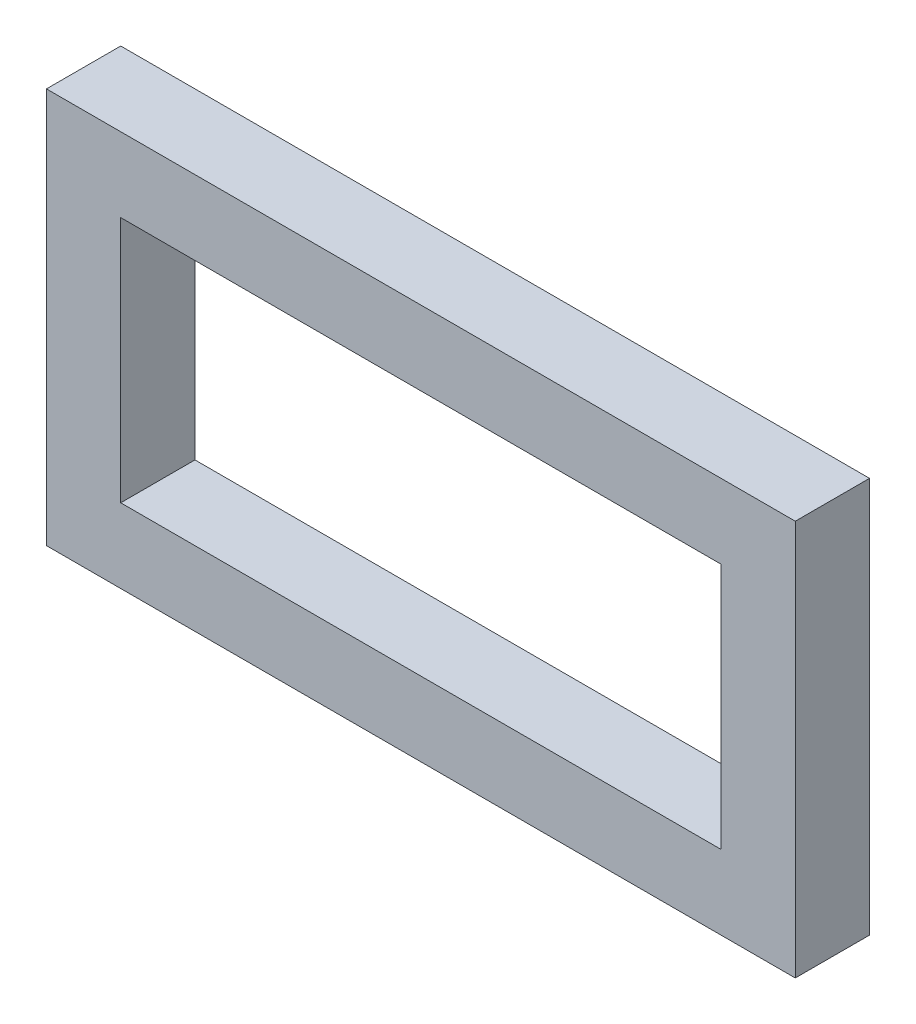
SolidWorks part; units mm, degrees
ref_plane "Front Plane" through (0, 0, 0) normal (0, 0, 1) x (1, 0, 0)
ref_plane "Top Plane" through (0, 0, 0) normal (0, 1, 0) x (1, 0, 0)
ref_plane "Right Plane" through (0, 0, 0) normal (1, 0, 0) x (0, 0, -1)
ref_plane "Plane1" through (0, 0, 1.398) normal (0, 0, 1) x (1, 0, 0)
sketch "Sketch1" plane through (0, 0, 1.398) normal (0, 0, 1) x (1, 0, 0)
  line L0 (1.398, 6.048) -> (12.698, 6.048)
  line L1 (12.698, 6.048) -> (12.698, 1.398)
  line L2 (12.698, 1.398) -> (1.398, 1.398)
  line L3 (1.398, 1.398) -> (1.398, 6.048)
  line L4 (0, 0) -> (14.098, 0)
  line L5 (14.098, 0) -> (14.098, 7.448)
  line L6 (14.098, 7.448) -> (0, 7.448)
  line L7 (0, 7.448) -> (0, 0)
extrude "Boss-Extrude1" add sketch "Sketch1" against normal blind 1.398
